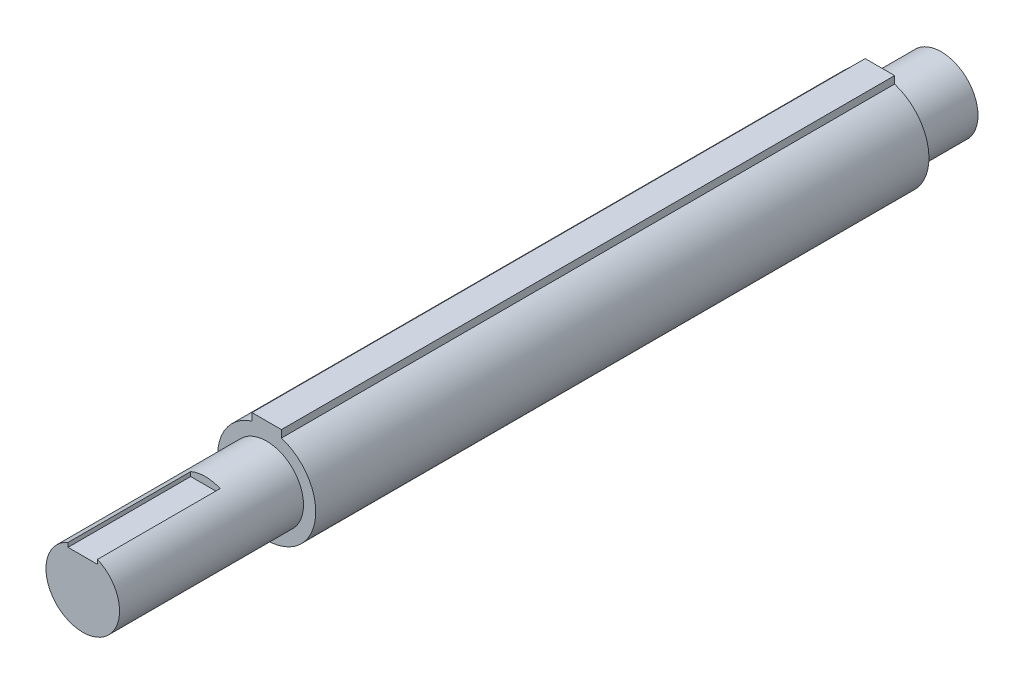
SolidWorks part; units mm, degrees
material "1023 Carbon Steel Sheet (SS)"
ref_plane "Front Plane" through (0, 0, 0) normal (0, 0, 1) x (1, 0, 0)
ref_plane "Top Plane" through (0, 0, 0) normal (0, 1, 0) x (1, 0, 0)
ref_plane "Right Plane" through (0, 0, 0) normal (1, 0, 0) x (0, 0, -1)
sketch "Sketch1" plane through (0, 0, 0) normal (0, 0, 1) x (1, 0, 0)
  line L0 (6, 19.0788) -> (6, 22.0788)
  line L1 (0, -48.9625) -> (0, 48.9625) construction
  line L2 (-6, 19.0788) -> (-6, 22.0788)
  line L5 (6, 19.0788) -> (6, 22.0788)
  line L6 (6, 22.0788) -> (-6, 22.0788)
  arc A0 (-6, 19.0788) -> (6, 19.0788) centre (0, 0) ccw
  point P5 (0, 0)
  point P6 (0, 0)
  dimension "D1" = 20
  dimension "D2" = 12
  dimension "D4" = 3
  dimension "D5" = 6
  dimension "D3" = 22.0788
extrude "Boss-Extrude1" add sketch "Sketch1" against normal blind 250 contours L1 A0 L0 L6 | A0 L1 L6 L2
sketch "Sketch2" plane through (0, 0, 0) normal (0, 0, 1) x (1, 0, 0)
  circle A0 centre (0, 0) radius 15
  dimension "D1" = 30
extrude "Boss-Extrude2" add sketch "Sketch2" along normal blind 75
sketch "Sketch3" plane through (0, 0, -250) normal (0, 0, -1) x (-1, 0, 0)
  circle A0 centre (0, 0) radius 15
  dimension "D1" = 30
extrude "Boss-Extrude3" add sketch "Sketch3" along normal blind 25
sketch "Sketch4" plane through (0, 0, 75) normal (0, 0, 1) x (1, 0, 0)
  line L1 (-6, 12) -> (6, 12)
  line L2 (-6, 12) -> (-6, 18)
  line L3 (-6, 18) -> (6, 18)
  line L4 (6, 12) -> (6, 18)
  line L5 (-6, 12) -> (6, 18) construction
  line L6 (-6, 18) -> (6, 12) construction
  circle A0 centre (0, 0) radius 15 construction
  circle A1 centre (0, 0) radius 15 construction
  point P0 (0, 15)
  dimension "D1" = 12
  dimension "D2" = 3
  dimension "D3" = 12
extrude "Cut-Extrude1" cut sketch "Sketch4" against normal blind 50
